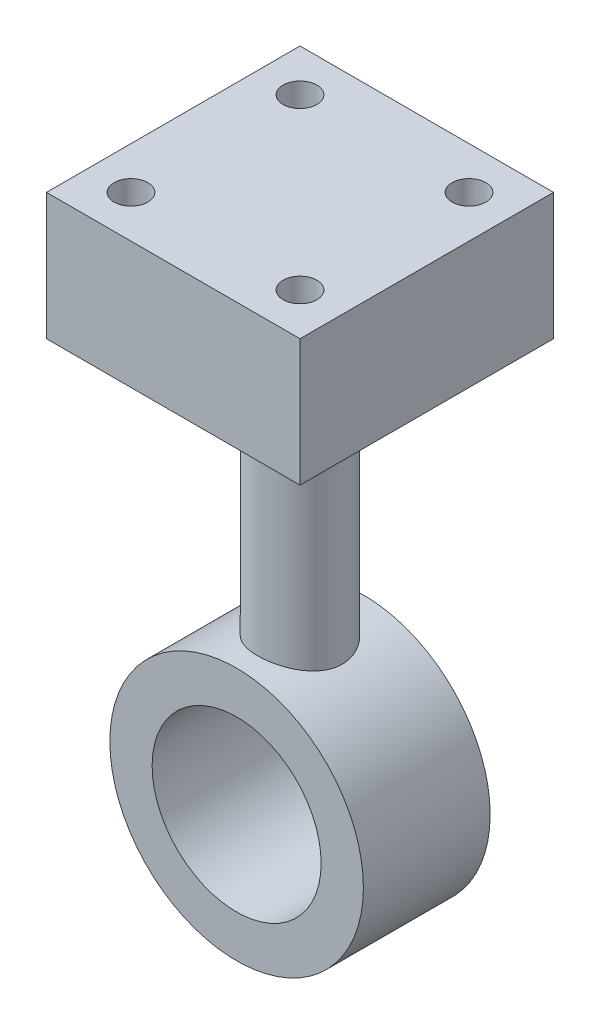
SolidWorks part; units mm, degrees
ref_plane "前视基准面" through (0, 0, 0) normal (0, 0, 1) x (1, 0, 0)
ref_plane "上视基准面" through (0, 0, 0) normal (0, 1, 0) x (1, 0, 0)
ref_plane "右视基准面" through (0, 0, 0) normal (1, 0, 0) x (0, 0, -1)
sketch "草图1" plane through (0, 0, 0) normal (0, 0, 1) x (1, 0, 0)
  circle A0 centre (0, 0) radius 10
  circle A1 centre (0, 0) radius 15
  dimension "D1" = 20
  dimension "D2" = 30
extrude "凸台-拉伸1" add sketch "草图1" along normal mid plane 15
ref_plane "基准面1" through (0, 45, 0) normal (0, 1, 0) x (1, 0, 0)
sketch "草图3" plane through (0, 45, 0) normal (0, 1, 0) x (1, 0, 0)
  circle A0 centre (0, 0) radius 5
  dimension "D1" = 10
extrude "凸台-拉伸2" add sketch "草图3" against normal up to surface (30 mm away)
sketch "草图4" plane through (0, 45, 0) normal (0, 1, 0) x (1, 0, 0)
  line L1 (-15, 15) -> (15, 15)
  line L2 (-15, 15) -> (-15, -15)
  line L3 (-15, -15) -> (15, -15)
  line L4 (15, 15) -> (15, -15)
  line L5 (0, -15) -> (0, 15) construction
  line L6 (-15, 0) -> (15, 0) construction
  point P0 (0, 0)
  dimension "D1" = 30
  dimension "D2" = 30
extrude "凸台-拉伸3" add sketch "草图4" along normal blind 15
sketch "草图5" plane through (0, 60, 0) normal (0, 1, 0) x (1, 0, 0)
  line L1 (-10, 10) -> (10, 10) construction
  line L2 (-10, 10) -> (-10, -10) construction
  line L3 (-10, -10) -> (10, -10) construction
  line L4 (10, 10) -> (10, -10) construction
  line L5 (0, -10) -> (0, 10) construction
  line L6 (-10, 0) -> (10, 0) construction
  circle A0 centre (10, 10) radius 2
  circle A1 centre (-10, 10) radius 2
  circle A2 centre (10, -10) radius 2
  circle A3 centre (-10, -10) radius 2
  point P0 (0, 0)
  dimension "D3" = 4
  dimension "D1" = 20
  dimension "D2" = 20
extrude "切除-拉伸1" cut sketch "草图5" against normal through all
